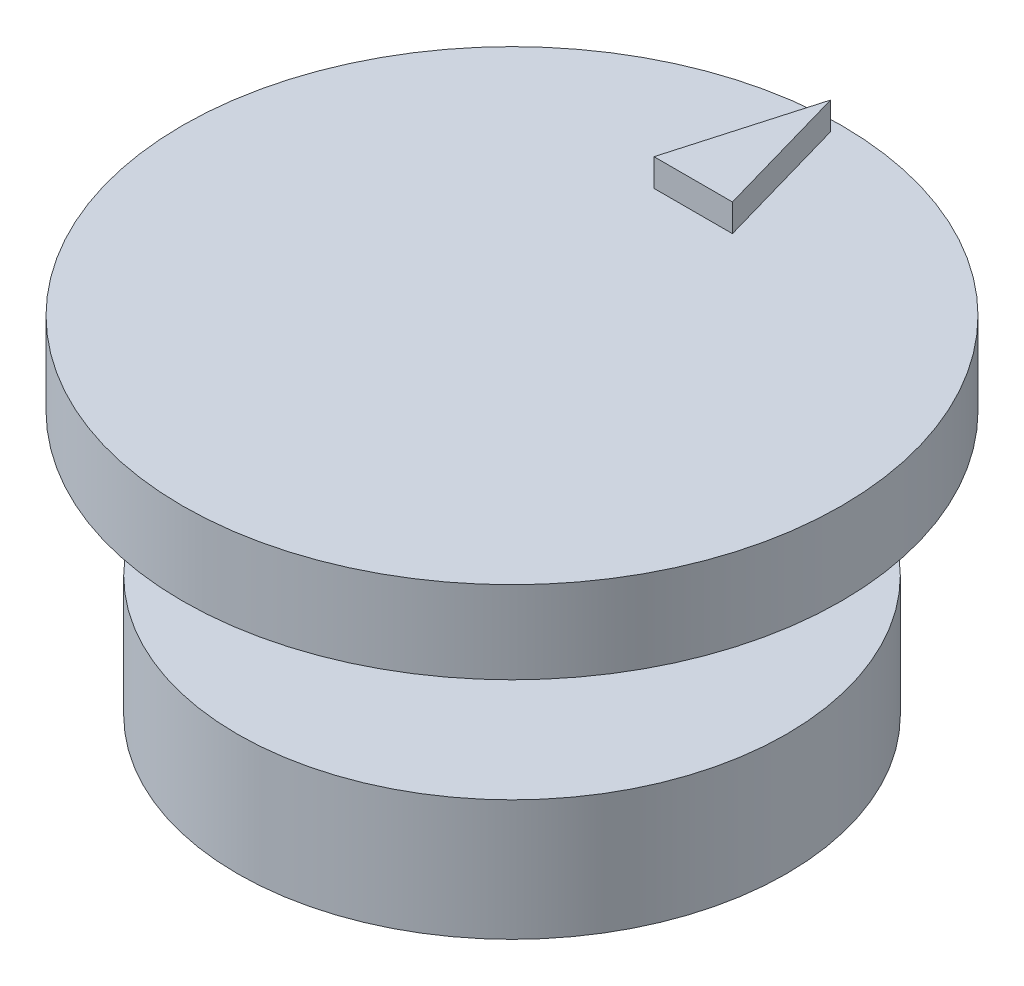
SolidWorks part; units mm, degrees
ref_plane "Front Plane" through (0, 0, 0) normal (0, 0, 1) x (1, 0, 0)
ref_plane "Top Plane" through (0, 0, 0) normal (0, 1, 0) x (1, 0, 0)
ref_plane "Right Plane" through (0, 0, 0) normal (1, 0, 0) x (0, 0, -1)
sketch "Sketch1" plane through (0, 0, 0) normal (0, 0, 1) x (1, 0, 0)
  line L0 (0, -20.8911) -> (0, -36.8931)
  line L1 (0, -36.8931) -> (12.7, -36.8931)
  line L2 (12.7, -36.8931) -> (12.7, -31.3051)
  line L3 (12.7, -31.3051) -> (3.175, -31.3051)
  line L4 (3.175, -31.3051) -> (3.175, -26.2251)
  line L5 (3.175, -26.2251) -> (12.7, -26.2251)
  line L6 (12.7, -26.2251) -> (12.7, -24.7011)
  line L7 (12.7, -24.7011) -> (15.24, -24.7011)
  line L8 (15.24, -24.7011) -> (15.24, -20.8911)
  line L9 (15.24, -20.8911) -> (0, -20.8911)
  dimension "D1" = 3.175
  dimension "D2" = 9.525
  dimension "D3" = 5.08
  dimension "D4" = 5.588
  dimension "D5" = 1.524
  dimension "D6" = 3.81
  dimension "D7" = 12.7
  dimension "D8" = 15.24
revolve "dial base shape" add sketch "Sketch1" angle 360 about L0
sketch "Sketch2" plane through (0, -20.8911, 0) normal (0, 1, 0) x (1, 0, 0)
  line L0 (0, 14.732) -> (-1.8139, 8.382)
  line L1 (-1.8139, 8.382) -> (1.8139, 8.382)
  line L2 (1.8139, 8.382) -> (0, 14.732)
  dimension "D1" = 6.35
  dimension "D2" = 8.382
  dimension "D3" = 6.604
  dimension "D4" = 6.604
extrude "arrow" add sketch "Sketch2" along normal blind 1.27
sketch "Sketch3" plane through (0, -36.8931, 0) normal (0, -1, 0) x (1, 0, 0)
  circle A0 centre (0, -9.8549) radius 2.286
  dimension "D1" = 4.572
extrude "flag" add sketch "Sketch3" along normal blind 6.35
ref_point "centre of flag base"
ref_point "centre of flag top"
